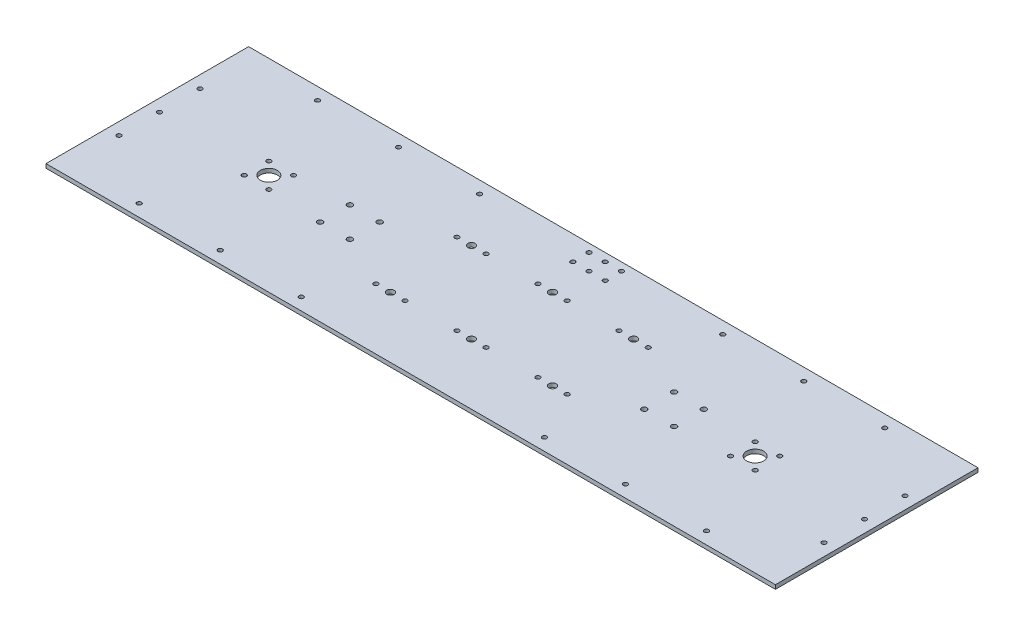
SolidWorks part; units mm, degrees
ref_plane "前视基准面" through (0, 0, 0) normal (0, 0, 1) x (1, 0, 0)
ref_plane "上视基准面" through (0, 0, 0) normal (0, 1, 0) x (1, 0, 0)
ref_plane "右视基准面" through (0, 0, 0) normal (1, 0, 0) x (0, 0, -1)
sketch "草图1" plane through (0, 0, 0) normal (0, 1, 0) x (1, 0, 0)
  line L0 (-900, 125) -> (0, 125) construction
  line L1 (0, 0) -> (-900, 0)
  line L2 (0, 0) -> (0, 250)
  line L3 (0, 250) -> (-900, 250)
  line L4 (-900, 0) -> (-900, 250)
  line L5 (-450, 250) -> (-450, 0) construction
  line L6 (-750, 125) -> (-810.1785, 185.1785) construction
  line L7 (-668.3848, 143.3848) -> (-650, 125) construction
  line L8 (-750, 172.7223) -> (-750, 125) construction
  line L9 (-650, 177.641) -> (-650, 125) construction
  circle A0 centre (-550, 175) radius 4.5
  circle A1 centre (-450, 175) radius 4.5
  circle A2 centre (-350, 175) radius 4.5
  circle A3 centre (-350, 75) radius 4.5
  circle A4 centre (-450, 75) radius 4.5
  circle A5 centre (-550, 75) radius 4.5
  circle A6 centre (-750, 125) radius 10.5
  circle A7 centre (-150, 125) radius 10.5
  circle A8 centre (-765.2028, 140.2028) radius 2.75
  circle A9 centre (-668.3848, 143.3848) radius 3.3
  circle A10 centre (-231.6152, 143.3848) radius 3.3
  circle A11 centre (-134.7972, 140.2028) radius 2.75
  circle A12 centre (-734.7972, 140.2028) radius 2.75
  circle A13 centre (-734.7972, 109.7972) radius 2.75
  circle A14 centre (-765.2028, 109.7972) radius 2.75
  circle A15 centre (-631.6152, 143.3848) radius 3.3
  circle A16 centre (-631.6152, 106.6152) radius 3.3
  circle A17 centre (-668.3848, 106.6152) radius 3.3
  circle A18 centre (-268.3848, 143.3848) radius 3.3
  circle A19 centre (-268.3848, 106.6152) radius 3.3
  circle A20 centre (-231.6152, 106.6152) radius 3.3
  circle A21 centre (-165.2028, 109.7972) radius 2.75
  circle A22 centre (-134.7972, 109.7972) radius 2.75
  circle A23 centre (-165.2028, 140.2028) radius 2.75
  point P7 (-750, 125)
  point P8 (-650, 125)
  point P9 (-450, 125)
  point P12 (-250, 125)
  point P13 (-150, 125)
  point P14 (-550, 175)
  point P15 (-450, 175)
  point P17 (-450, 75)
  point P18 (-550, 75)
  point P19 (-350, 175)
  point P20 (-350, 75)
  point P36 (-765.2028, 140.2028)
  point P43 (-668.3848, 143.3848)
  dimension "D7" = 9
  dimension "D8" = 21
  dimension "D9" = 21
  dimension "D10" = 5.5
  dimension "D14" = 6.6
  dimension "D15" = 26
  dimension "D1" = 900
  dimension "D2" = 250
  dimension "D3" = 150
  dimension "D4" = 100
  dimension "D5" = 100
  dimension "D6" = 50
  dimension "D11" = 45
  dimension "D12" = 21.5
  dimension "D13" = 45
extrude "凸台-拉伸1" add sketch "草图1" along normal blind 5
sketch "草图2" plane through (0, 5, 0) normal (0, 1, 0) x (1, 0, 0)
  line L0 (-450, 250) -> (-450, 0) construction
  line L1 (0, 250) -> (-900, 250) construction
  line L2 (-900, 0) -> (0, 0) construction
  line L3 (-885, 250) -> (-885, 0) construction
  line L4 (-430, 220) -> (-470, 220) construction
  line L5 (-430, 220) -> (-430, 240) construction
  line L6 (-430, 240) -> (-470, 240) construction
  line L7 (-470, 220) -> (-470, 240) construction
  line L8 (-430, 220) -> (-470, 240) construction
  line L9 (-430, 240) -> (-470, 220) construction
  line L10 (-900, 250) -> (-900, 0) construction
  line L11 (-900, 125) -> (-590.7904, 125) construction
  circle A0 centre (-470, 240) radius 2.75
  circle A1 centre (-430, 240) radius 2.75
  circle A2 centre (-430, 220) radius 2.75
  circle A3 centre (-470, 220) radius 2.75
  circle A4 centre (-450, 220) radius 2.75
  circle A5 centre (-450, 240) radius 2.75
  circle A6 centre (-885, 175) radius 2.75
  circle A7 centre (-885, 125) radius 2.75
  circle A8 centre (-885, 75) radius 2.75
  circle A9 centre (-15, 175) radius 2.75
  circle A10 centre (-15, 125) radius 2.75
  circle A11 centre (-15, 75) radius 2.75
  point P6 (-450, 230)
  dimension "D4" = 5.5
  dimension "D6" = 5.5
  dimension "D7" = 50
  dimension "D1" = 40
  dimension "D2" = 20
  dimension "D3" = 10
  dimension "D5" = 15
extrude "切除-拉伸1" cut sketch "草图2" against normal through all
sketch "草图3" plane through (0, 5, 0) normal (0, 1, 0) x (1, 0, 0)
  line L0 (-550, 175) -> (-350, 175) construction
  line L1 (-450, 250) -> (-450, 175) construction
  line L2 (0, 250) -> (-900, 250) construction
  line L3 (-900, 125) -> (0, 125) construction
  line L4 (-900, 250) -> (-900, 0) construction
  line L5 (0, 0) -> (0, 250) construction
  circle A0 centre (-568, 175) radius 2.75
  circle A1 centre (-532, 175) radius 2.75
  circle A2 centre (-468, 175) radius 2.75
  circle A4 centre (-432, 175) radius 2.75
  circle A5 centre (-368, 175) radius 2.75
  circle A6 centre (-332, 175) radius 2.75
  circle A7 centre (-332, 75) radius 2.75
  circle A8 centre (-368, 75) radius 2.75
  circle A9 centre (-432, 75) radius 2.75
  circle A10 centre (-468, 75) radius 2.75
  circle A11 centre (-532, 75) radius 2.75
  circle A12 centre (-568, 75) radius 2.75
  dimension "D1" = 5.5
  dimension "D2" = 18
  dimension "D3" = 18
  dimension "D4" = 18
extrude "切除-拉伸2" cut sketch "草图3" against normal through all
sketch "草图5" plane through (0, 5, 0) normal (0, 1, 0) x (1, 0, 0)
  line L0 (-900, 15) -> (0, 15) construction
  line L1 (-900, 250) -> (-900, 0) construction
  line L2 (0, 0) -> (0, 250) construction
  line L3 (-900, 235) -> (0, 235) construction
  line L4 (0, 250) -> (-900, 250) construction
  line L5 (-900, 0) -> (0, 0) construction
  line L6 (-450, 250) -> (-450, 0) construction
  line L7 (-900, 125) -> (-582.915, 125) construction
  circle A0 centre (-800, 235) radius 2.75
  circle A1 centre (-700, 235) radius 2.75
  circle A2 centre (-600, 235) radius 2.75
  circle A3 centre (-600, 15) radius 2.75
  circle A4 centre (-700, 15) radius 2.75
  circle A5 centre (-800, 15) radius 2.75
  circle A6 centre (-300, 15) radius 2.75
  circle A7 centre (-200, 15) radius 2.75
  circle A8 centre (-100, 15) radius 2.75
  circle A9 centre (-300, 235) radius 2.75
  circle A10 centre (-200, 235) radius 2.75
  circle A11 centre (-100, 235) radius 2.75
  dimension "D3" = 5.5
  dimension "D4" = 5.5
  dimension "D6" = 100
  dimension "D7" = 100
  dimension "D1" = 15
  dimension "D2" = 15
  dimension "D5" = 100
extrude "切除-拉伸4" cut sketch "草图5" against normal through all
